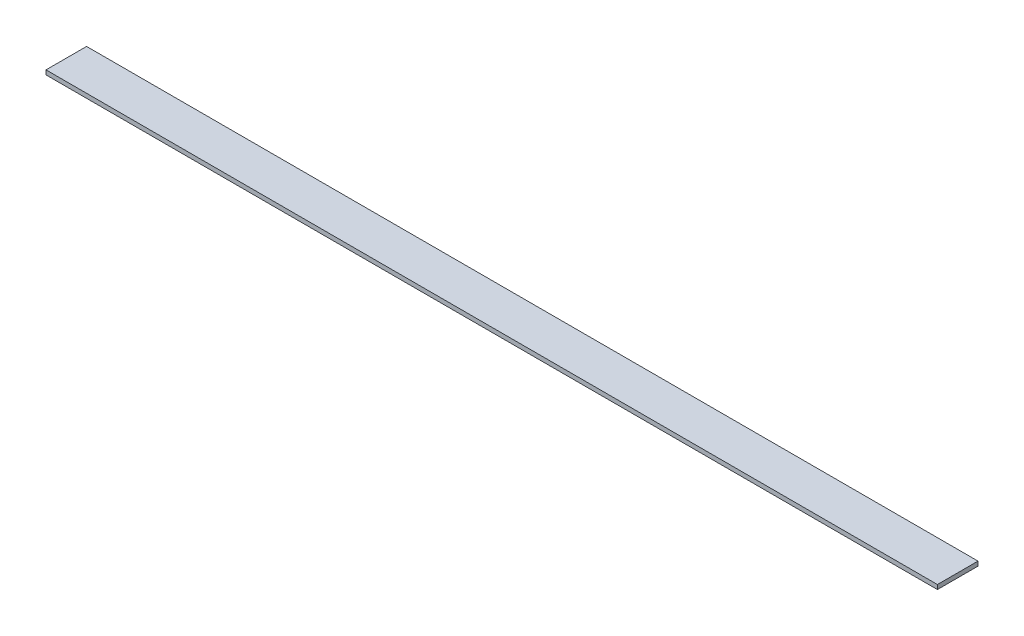
SolidWorks part; units mm, degrees
material "AISI Type 316L stainless steel"
ref_plane "Front Plane" through (0, 0, 0) normal (0, 0, 1) x (1, 0, 0)
ref_plane "Top Plane" through (0, 0, 0) normal (0, 1, 0) x (1, 0, 0)
ref_plane "Right Plane" through (0, 0, 0) normal (1, 0, 0) x (0, 0, -1)
sketch "Sketch1" plane through (0, 0, 0) normal (0, 1, 0) x (1, 0, 0)
  line L1 (-203.2, 9.25) -> (203.2, 9.25)
  line L2 (-203.2, 9.25) -> (-203.2, -9.25)
  line L3 (-203.2, -9.25) -> (203.2, -9.25)
  line L4 (203.2, 9.25) -> (203.2, -9.25)
  line L5 (-203.2, 9.25) -> (203.2, -9.25) construction
  line L6 (-203.2, -9.25) -> (203.2, 9.25) construction
  point P0 (0, 0)
  dimension "D1" = 18.5
  dimension "D2" = 406.4
extrude "Boss-Extrude1" add sketch "Sketch1" along normal blind 2
